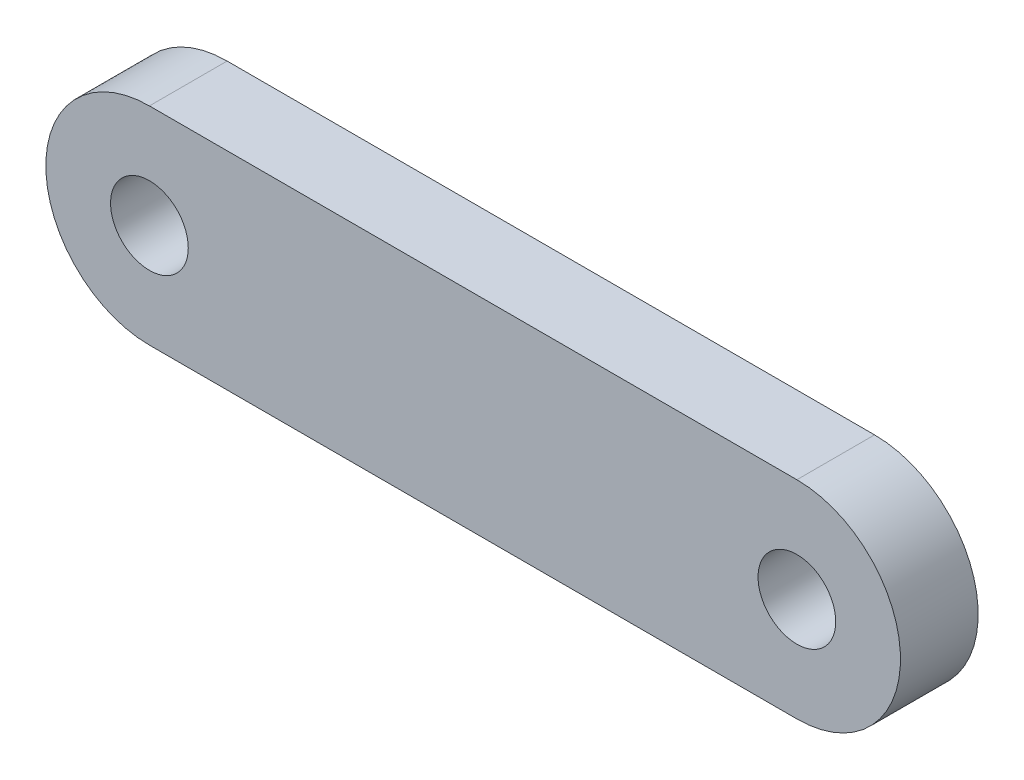
SolidWorks part; units mm, degrees
ref_plane "Front Plane" through (0, 0, 0) normal (0, 0, 1) x (1, 0, 0)
ref_plane "Top Plane" through (0, 0, 0) normal (0, 1, 0) x (1, 0, 0)
ref_plane "Right Plane" through (0, 0, 0) normal (1, 0, 0) x (0, 0, -1)
sketch "Sketch1" plane through (0, 0, 0) normal (0, 0, 1) x (1, 0, 0)
  line L0 (-23.3034, 0) -> (12.6332, 0) construction
  line L1 (-25, 4) -> (0, 4)
  line L2 (-25, -4) -> (0, -4)
  circle A0 centre (0, 0) radius 1.5
  circle A1 centre (-25, 0) radius 1.5
  arc A2 (-25, 4) -> (-25, -4) centre (-25, 0) ccw
  arc A3 (0, -4) -> (0, 4) centre (0, 0) ccw
  dimension "D1" = 3
  dimension "D2" = 3
  dimension "D4" = 8
  dimension "D5" = 8
  dimension "D3" = 25
extrude "Boss-Extrude1" add sketch "Sketch1" along normal blind 3
